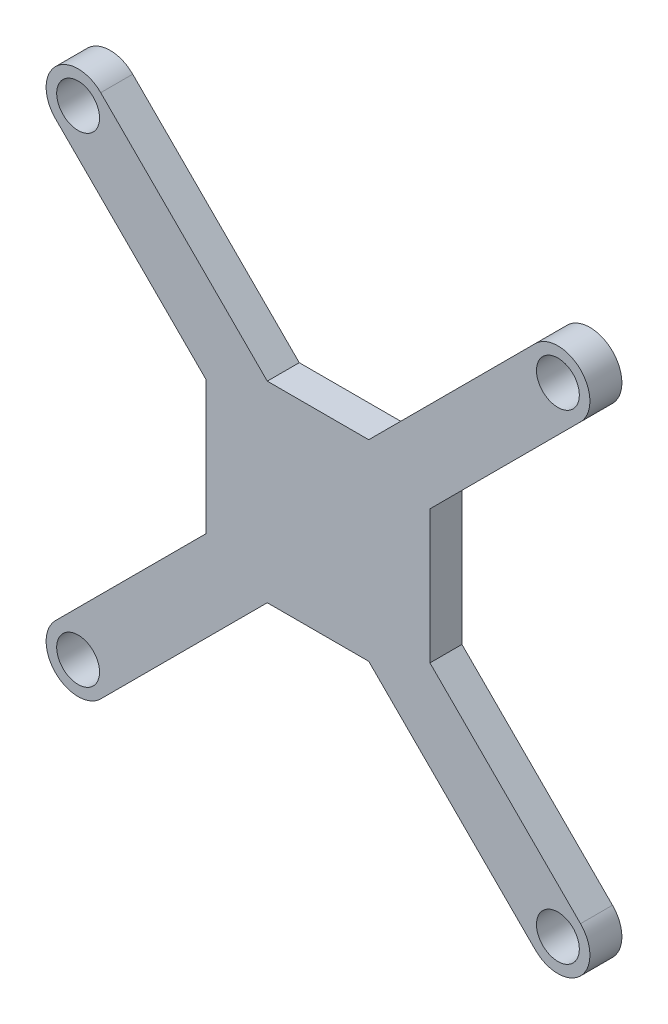
SolidWorks part; units mm, degrees
ref_plane "前视基准面" through (0, 0, 0) normal (0, 0, 1) x (1, 0, 0)
ref_plane "上视基准面" through (0, 0, 0) normal (0, 1, 0) x (1, 0, 0)
ref_plane "右视基准面" through (0, 0, 0) normal (1, 0, 0) x (0, 0, -1)
sketch "草图1" plane through (0, 0, 0) normal (0, 0, 1) x (1, 0, 0)
  line L0 (-0.0824, 10.8495) -> (-0.0824, -4.1505) construction
  line L1 (-17.5824, -4.1505) -> (-0.0824, -4.1505) construction
  line L2 (33.8821, 36.885) -> (7.8465, 10.8495)
  line L3 (40.9531, 29.8139) -> (17.4176, 6.2784)
  line L4 (17.4176, -14.5795) -> (17.4176, 6.2784)
  line L5 (40.9531, -38.115) -> (17.4176, -14.5795)
  line L6 (-34.0469, -45.1861) -> (-8.0113, -19.1505)
  line L7 (-41.1179, -38.115) -> (-17.5824, -14.5795)
  line L8 (-17.5824, -14.5795) -> (-17.5824, 6.2784)
  line L9 (-8.0113, 10.8495) -> (7.8465, 10.8495)
  line L10 (-8.0113, -19.1505) -> (7.8465, -19.1505)
  line L11 (33.8821, -45.1861) -> (7.8465, -19.1505)
  line L13 (-41.1179, 29.8139) -> (-17.5824, 6.2784)
  line L14 (-34.0469, 36.885) -> (-8.0113, 10.8495)
  arc A0 (-34.0469, 36.885) -> (-41.1179, 29.8139) centre (-37.5824, 33.3495) ccw
  arc A1 (33.8821, 36.885) -> (40.9531, 29.8139) centre (37.4176, 33.3495) cw
  arc A2 (33.8821, -45.1861) -> (40.9531, -38.115) centre (37.4176, -41.6505) ccw
  arc A3 (-34.0469, -45.1861) -> (-41.1179, -38.115) centre (-37.5824, -41.6505) cw
  point P12 (-0.0824, -4.1505)
  point P25 (17.4176, -4.1505)
  dimension "D1" = 10
extrude "凸台-拉伸1" add sketch "草图1" along normal blind 5
sketch "草图4" plane through (0, 0, 5) normal (0, 0, 1) x (1, 0, 0)
  circle A0 centre (-37.5824, 33.3495) radius 3.35
  circle A1 centre (37.4176, 33.3495) radius 3.35
  circle A2 centre (37.4176, -41.6505) radius 3.35
  circle A3 centre (-37.5824, -41.6505) radius 3.35
  dimension "D1" = 6.7
  dimension "D2" = 6.7
  dimension "D3" = 6.7
  dimension "D4" = 6.7
extrude "切除-拉伸1" cut sketch "草图4" against normal blind 5
